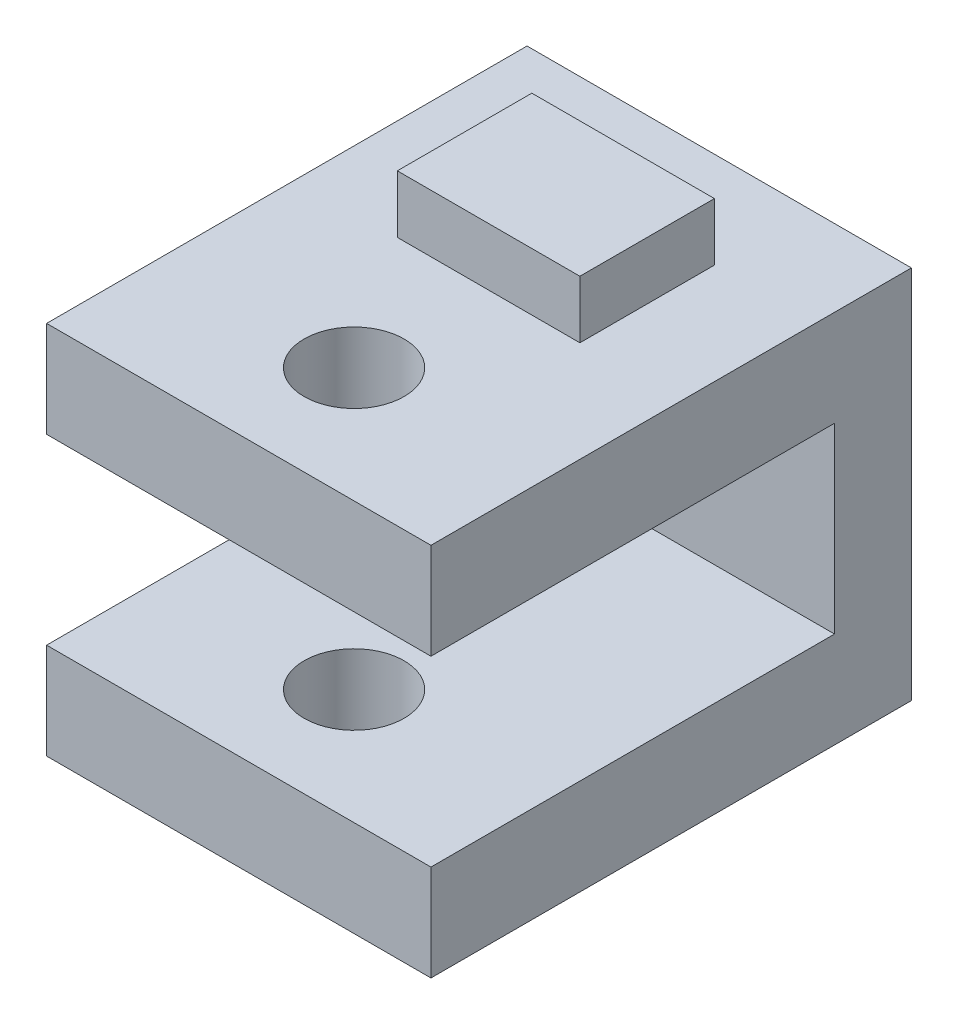
SolidWorks part; units mm, degrees
ref_plane "前视基准面" through (0, 0, 0) normal (0, 0, 1) x (1, 0, 0)
ref_plane "上视基准面" through (0, 0, 0) normal (0, 1, 0) x (1, 0, 0)
ref_plane "右视基准面" through (0, 0, 0) normal (1, 0, 0) x (0, 0, -1)
sketch "草图1" plane through (0, 0, 0) normal (0, 0, 1) x (1, 0, 0)
  line L1 (-10, 9.75) -> (10, 9.75)
  line L2 (-10, 9.75) -> (-10, -9.75)
  line L3 (-10, -9.75) -> (10, -9.75)
  line L4 (10, 9.75) -> (10, -9.75)
  point P4 (0, 9.75)
  point P6 (-10, 0)
  dimension "D1" = 20
  dimension "D2" = 19.5
extrude "凸台-拉伸1" add sketch "草图1" along normal blind 4
sketch "草图2" plane through (0, 0, 4) normal (0, 0, 1) x (1, 0, 0)
  line L0 (10, -9.75) -> (10, 9.75) construction
  line L1 (-10, 9.75) -> (10, 9.75)
  line L2 (-10, 9.75) -> (-10, 4.75)
  line L3 (-10, 4.75) -> (10, 4.75)
  line L4 (10, 9.75) -> (10, 4.75)
  line L5 (-10, 9.75) -> (-10, -9.75) construction
  line L6 (10, -9.75) -> (-10, -9.75)
  line L7 (10, -9.75) -> (10, -4.75)
  line L8 (10, -4.75) -> (-10, -4.75)
  line L9 (-10, -9.75) -> (-10, -4.75)
  dimension "D1" = 5
  dimension "D2" = 5
extrude "凸台-拉伸2" add sketch "草图2" along normal blind 21
sketch "草图3" plane through (0, 9.75, 0) normal (0, 1, 0) x (1, 0, 0)
  line L0 (10, 0) -> (-10, 0) construction
  line L1 (-4.75, -5) -> (4.75, -5)
  line L2 (-4.75, -5) -> (-4.75, -12)
  line L3 (-4.75, -12) -> (4.75, -12)
  line L4 (4.75, -5) -> (4.75, -12)
  point P4 (0, -5)
  dimension "D1" = 9.5
  dimension "D2" = 7
  dimension "D3" = 5
extrude "凸台-拉伸3" add sketch "草图3" along normal blind 3
sketch "草图4" plane through (0, -9.75, 0) normal (0, -1, 0) x (1, 0, 0)
  line L0 (-10, 0) -> (10, 0) construction
  line L1 (4.75, 5) -> (-4.75, 5)
  line L2 (4.75, 5) -> (4.75, 12)
  line L3 (4.75, 12) -> (-4.75, 12)
  line L4 (-4.75, 5) -> (-4.75, 12)
  point P4 (0, 12)
  dimension "D1" = 9.5
  dimension "D2" = 7
  dimension "D3" = 5
extrude "凸台-拉伸4" add sketch "草图4" along normal blind 3
sketch "草图5" plane through (0, 9.75, 0) normal (0, 1, 0) x (1, 0, 0)
  line L0 (10, -25) -> (-10, -25) construction
  circle A0 centre (0, -19) radius 2.6
  point P2 (0, 0)
  point P4 (0, 0)
  dimension "D1" = 5.2
  dimension "D2" = 6
extrude "切除-拉伸1" cut sketch "草图5" against normal through all
sketch "草图6" plane through (0, 0, 0) normal (0, 0, -1) x (-1, 0, 0)
  circle A0 centre (0, 0) radius 2.6
  dimension "D1" = 5.2
extrude "切除-拉伸2" cut sketch "草图6" against normal through all
